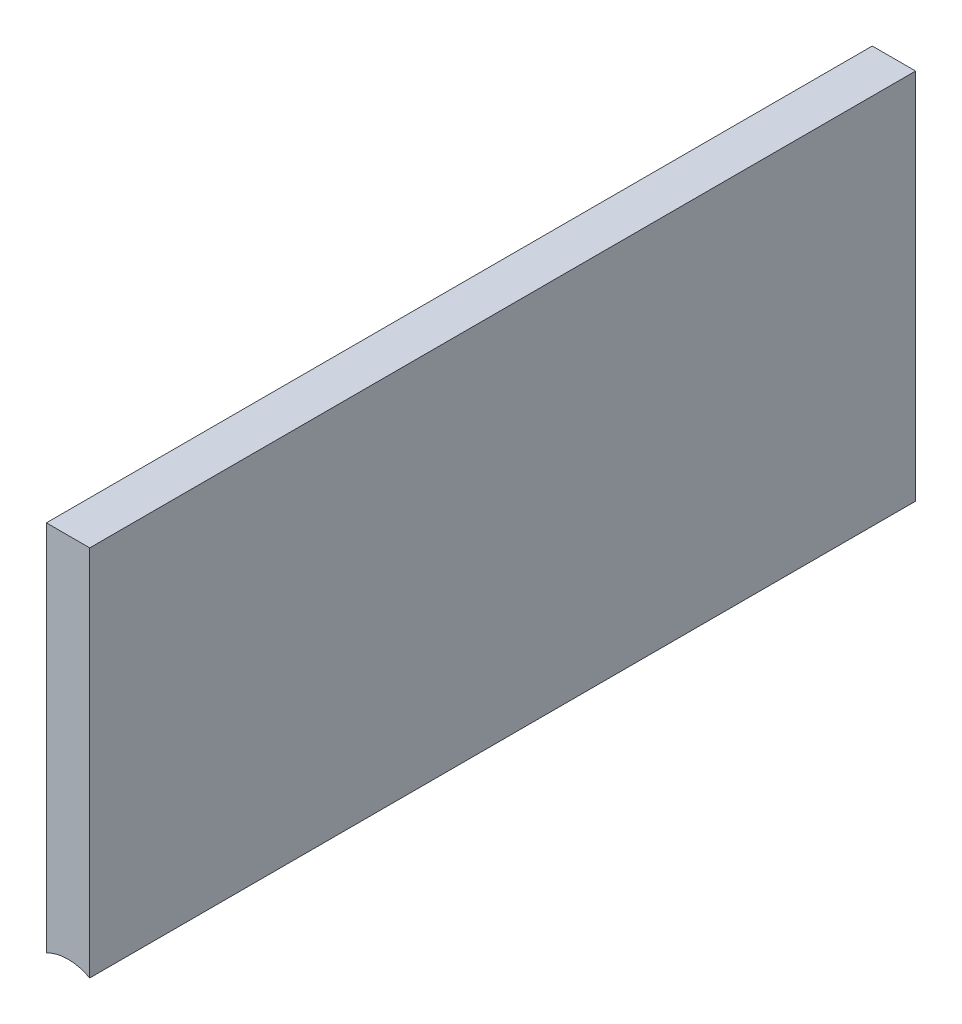
SolidWorks part; units mm, degrees
ref_plane "Alzado" through (0, 0, 0) normal (0, 0, 1) x (1, 0, 0)
ref_plane "Planta" through (0, 0, 0) normal (0, 1, 0) x (1, 0, 0)
ref_plane "Vista lateral" through (0, 0, 0) normal (1, 0, 0) x (0, 0, -1)
sketch "Croquis1" plane through (0, 0, 0) normal (1, 0, 0) x (0, 0, -1)
  line L1 (0, 0) -> (57.15, 0)
  line L2 (0, 0) -> (0, 25.4)
  line L3 (0, 25.4) -> (57.15, 25.4)
  line L4 (57.15, 0) -> (57.15, 25.4)
  dimension "D1" = 57.15
  dimension "D2" = 25.4
extrude "Saliente-Extruir1" add sketch "Croquis1" along normal blind 3
sketch "Croquis2" plane through (0, 0, 0) normal (0, 0, 1) x (1, 0, 0)
  line L3 (0, 0) -> (3, 0)
  line L4 (0, 0) -> (0, -0.3767)
  line L6 (3, 0) -> (3, -0.3767)
  arc A0 (3, -0.3767) -> (0, -0.3767) centre (1.5, -3.175) ccw
  line M4 (0, 0) -> (3, 0)
  dimension "D1" = 3.175
extrude "Saliente-Extruir2" add sketch "Croquis2" against normal up to surface (57.15 mm away) contours A0 L6 L3 | A0 L4 M4 up to face at (1.5, 12.7, -57.15)
